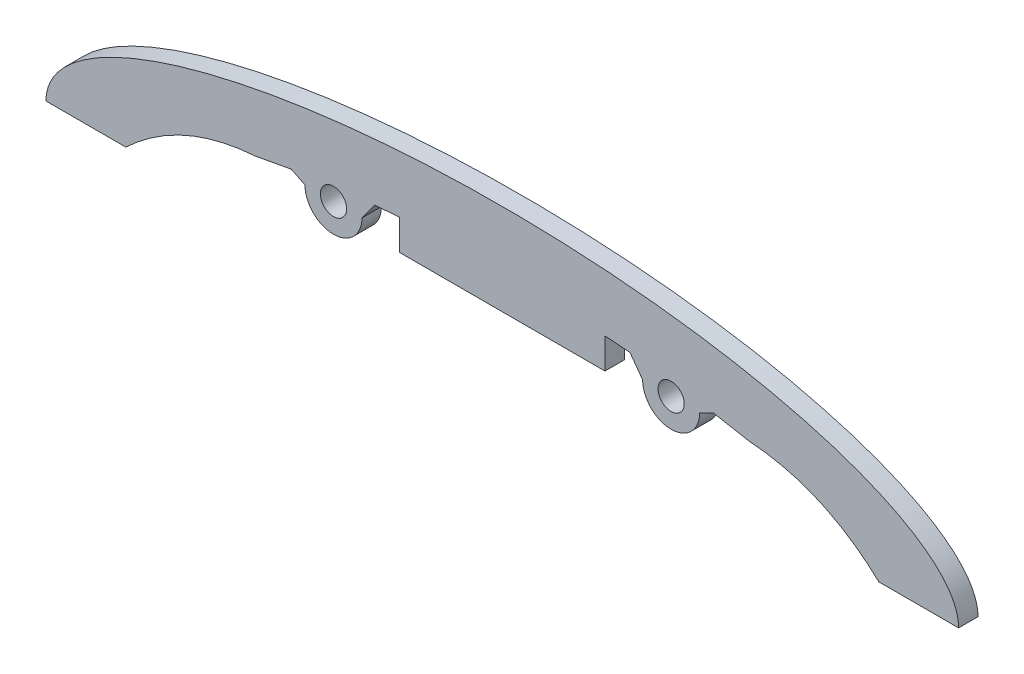
SolidWorks part; units mm, degrees
ref_plane "Płaszczyzna przednia" through (0, 0, 0) normal (0, 0, 1) x (1, 0, 0)
ref_plane "Płaszczyzna górna" through (0, 0, 0) normal (0, 1, 0) x (1, 0, 0)
ref_plane "Płaszczyzna prawa" through (0, 0, 0) normal (1, 0, 0) x (0, 0, -1)
sketch "Szkic1" plane through (0, 0, 0) normal (0, 0, 1) x (1, 0, 0)
  line L0 (-40, 0) -> (-33, 0)
  line L5 (33, 0) -> (40, 0)
  line L6 (-21.6102, 5) -> (21.6102, 5) construction
  line L7 (-40, 0) -> (40, 0) construction
  line L8 (0, 26.284) -> (0, -11.2038) construction
  line L9 (-12.3, 4.9798) -> (-11.2, 6.5001)
  line L11 (-9, 6.6798) -> (-9, 4)
  line L12 (-9, 4) -> (9, 4)
  line L13 (9, 6.6798) -> (9, 4)
  line L14 (-17.3, 4.9798) -> (-18.5, 5.5751)
  line L15 (12.3, 4.9798) -> (11.2, 6.5001)
  line L16 (17.3, 4.9798) -> (18.5, 5.5751)
  arc A2 (-17.3, 4.9798) -> (-12.3, 4.9798) centre (-14.8, 4.9798) ccw
  arc A3 (12.3, 4.9798) -> (17.3, 4.9798) centre (14.8, 4.9798) ccw
  ellipse E0 centre (0, 0) end of major axis (-40, 0) minor radius 12 (40, 0) -> (-40, 0) ccw
  spline S0 degree 1 poles (21.6102, 5) (-21.6102, 5) knots 0 0 1 1 construction
  spline S1 degree 3 poles (21.6102, 5) (21.218, 5.0807) (20.4395, 5.2344) (19.4951, 5.406) (18.742, 5.5353) (17.912, 5.6726) (15.627, 6.023) (13.0948, 6.3274) (10.8372, 6.5336) (10.1054, 6.5952) (9.3703, 6.6535) (7.9311, 6.7574) (4.7685, 6.9358) (0, 7.0436) (-4.7685, 6.9358) (-7.9311, 6.7574) (-9.3703, 6.6535) (-10.1054, 6.5952) (-10.8372, 6.5336) (-13.0948, 6.3274) (-15.627, 6.023) (-17.912, 5.6726) (-18.742, 5.5353) (-19.4951, 5.406) (-20.4395, 5.2344) (-21.218, 5.0807) (-21.6102, 5) knots -2.17176 -2.17176 -2.17176 -2.17176 -2.1342 -2.096639 -2.084153 -2.065373 -2.021519 -1.881328 -1.851592 -1.836724 -1.821856 -1.792121 -1.721037 -1.570796 -1.420555 -1.349472 -1.319736 -1.304868 -1.290001 -1.260265 -1.120074 -1.07622 -1.05744 -1.044953 -1.007393 -0.969833 -0.969833 -0.969833 -0.969833
  spline S2 degree 2 poles (-21.6102, 5) (-28.2034, 4.5386) (-33, 0) knots 0 0 0 1 1 1
  spline S3 degree 2 poles (21.6102, 5) (28.2034, 4.5386) (33, 0) knots 0 0 0 1 1 1
  point P24 (17.3, 4.5564)
  point P31 (17.3, 5.2018)
  point P32 (12.4, 4.4553)
  point P33 (11.1, 6.5001)
  point P34 (0, 0)
  point P35 (0, 0)
  point P36 (0, 0)
  point P37 (17.3, 4.4221)
  point P38 (0, 0)
  point P39 (0, 0)
  point P40 (0, 0)
  point P41 (0, 0)
  point P42 (-12.0975, 4.9798)
  point P43 (11.1999, 6.5001)
  dimension "D8" = 12.7
  dimension "D9" = 12.7
  dimension "D14" = 5
  dimension "D15" = 5
  dimension "D2" = 80
  dimension "D3" = 7
  dimension "D4" = 7
  dimension "D5" = 12
  dimension "D6" = 3.5
  dimension "D7" = 1.5
  dimension "D10" = 3.5
  dimension "D11" = 8
  dimension "D12" = 9
  dimension "D13" = 9
  dimension "D16" = 3.7
  dimension "D17" = 2.2
  dimension "D18" = 3.3
  dimension "D19" = 2.2
  dimension "D20" = 8.3
  dimension "D21" = 1.7
  dimension "D22" = 3.3
  dimension "D23" = 3.7
  dimension "D1" = 5
extrude "Dodanie-wyciągnięcie1" add sketch "Szkic1" along normal blind 1.7
sketch "Szkic2" plane through (0, 0, 1.7) normal (0, 0, 1) x (1, 0, 0)
  circle A0 centre (-14.8, 4.9798) radius 1.15
  circle A1 centre (14.8, 4.9798) radius 1.15
  dimension "D1" = 2.3
  dimension "D2" = 2.3
extrude "Wytnij-wyciągnięcie1" cut sketch "Szkic2" against normal through all
